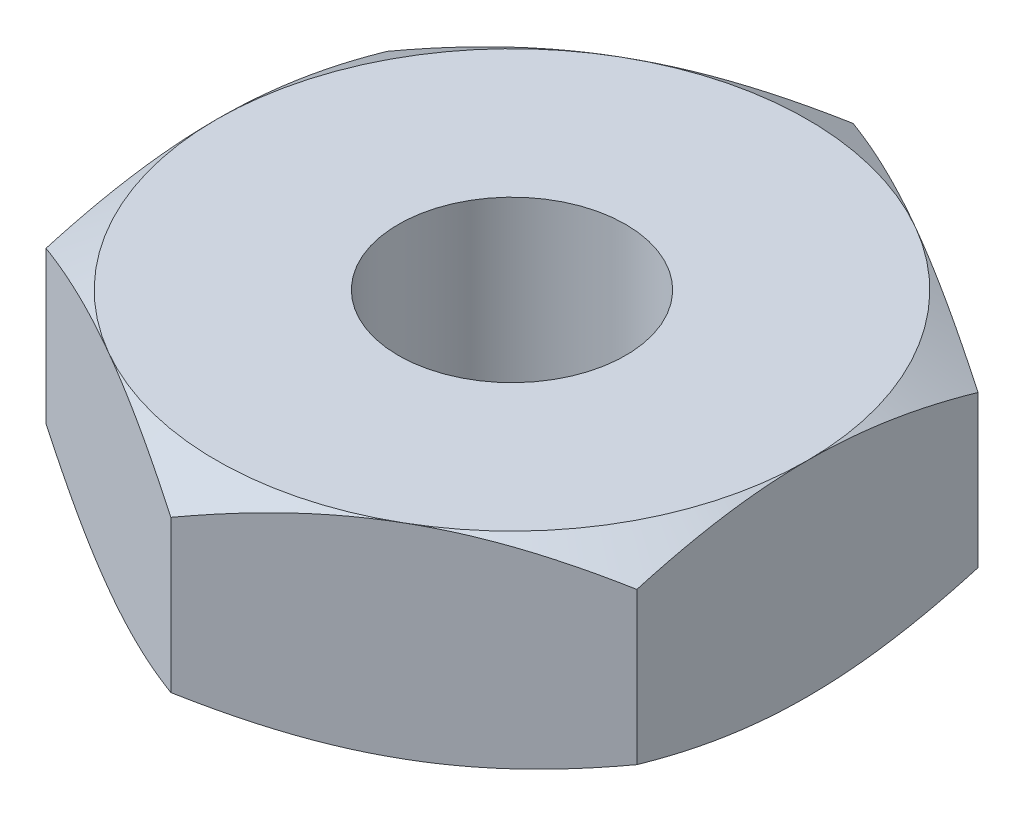
SolidWorks part; units mm, degrees
ref_plane "Front Plane" through (0, 0, 0) normal (0, 0, 1) x (1, 0, 0)
ref_plane "Top Plane" through (0, 0, 0) normal (0, 1, 0) x (1, 0, 0)
ref_plane "Right Plane" through (0, 0, 0) normal (1, 0, 0) x (0, 0, -1)
sketch "Sketch1" plane through (0, 0, 0) normal (0, 1, 0) x (1, 0, 0)
  line L1 (0, 1.8764) -> (-1.625, 0.9382)
  line L2 (-1.625, 0.9382) -> (-1.625, -0.9382)
  line L3 (-1.625, -0.9382) -> (0, -1.8764)
  line L4 (0, -1.8764) -> (1.625, -0.9382)
  line L5 (1.625, -0.9382) -> (1.625, 0.9382)
  line L6 (1.625, 0.9382) -> (0, 1.8764)
  circle A0 centre (0, 0) radius 1.625 construction
  circle A1 centre (0, 0) radius 0.625
  dimension "D1" = 1.25
  dimension "D2" = 3.25
extrude "Boss-Extrude1" add sketch "Sketch1" along normal blind 1.125
sketch "Sketch2" plane through (0, 1.125, 0) normal (0, 1, 0) x (1, 0, 0)
  circle A0 centre (0, 0) radius 1.625 construction
  circle A1 centre (0, 0) radius 1.625
extrude "Cut-Extrude1" cut sketch "Sketch2" against normal blind 2 draft 60 flip side to cut
ref_plane "Plane1" through (0, 0.5625, 0) normal (0, 1, 0) x (1, 0, 0)
mirror "Mirror1" about plane through (0, 0.5625, 0) normal (0, 1, 0) of "Cut-Extrude1"
